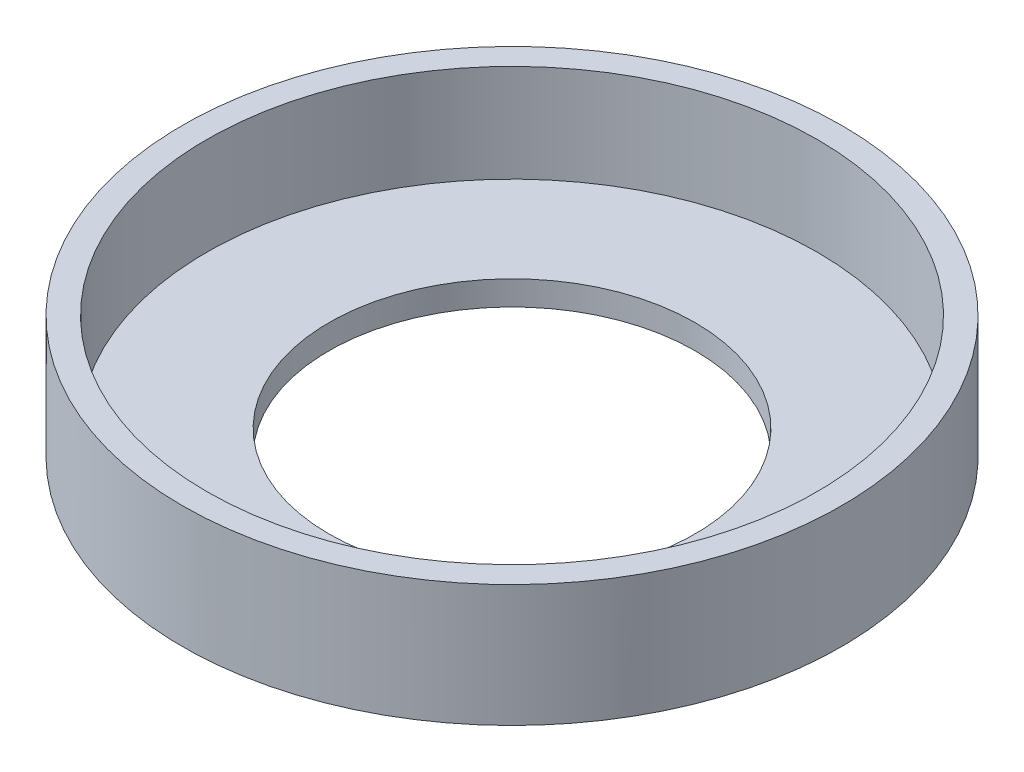
SolidWorks part; units mm, degrees
ref_plane "Front Plane" through (0, 0, 0) normal (0, 0, 1) x (1, 0, 0)
ref_plane "Top Plane" through (0, 0, 0) normal (0, 1, 0) x (1, 0, 0)
ref_plane "Right Plane" through (0, 0, 0) normal (1, 0, 0) x (0, 0, -1)
sketch "Sketch1" plane through (0, 0, 0) normal (0, 1, 0) x (1, 0, 0)
  circle A0 centre (0, 0) radius 13.5
  circle A1 centre (0, 0) radius 12.5
  dimension "D1" = 25
  dimension "D2" = 27
extrude "Boss-Extrude1" add sketch "Sketch1" along normal blind 4
sketch "Sketch2" plane through (0, 0, 0) normal (0, -1, 0) x (1, 0, 0)
  circle A0 centre (0, 0) radius 13.5
  circle A1 centre (0, 0) radius 7.5
  dimension "D1" = 15
extrude "Boss-Extrude2" add sketch "Sketch2" along normal blind 1
